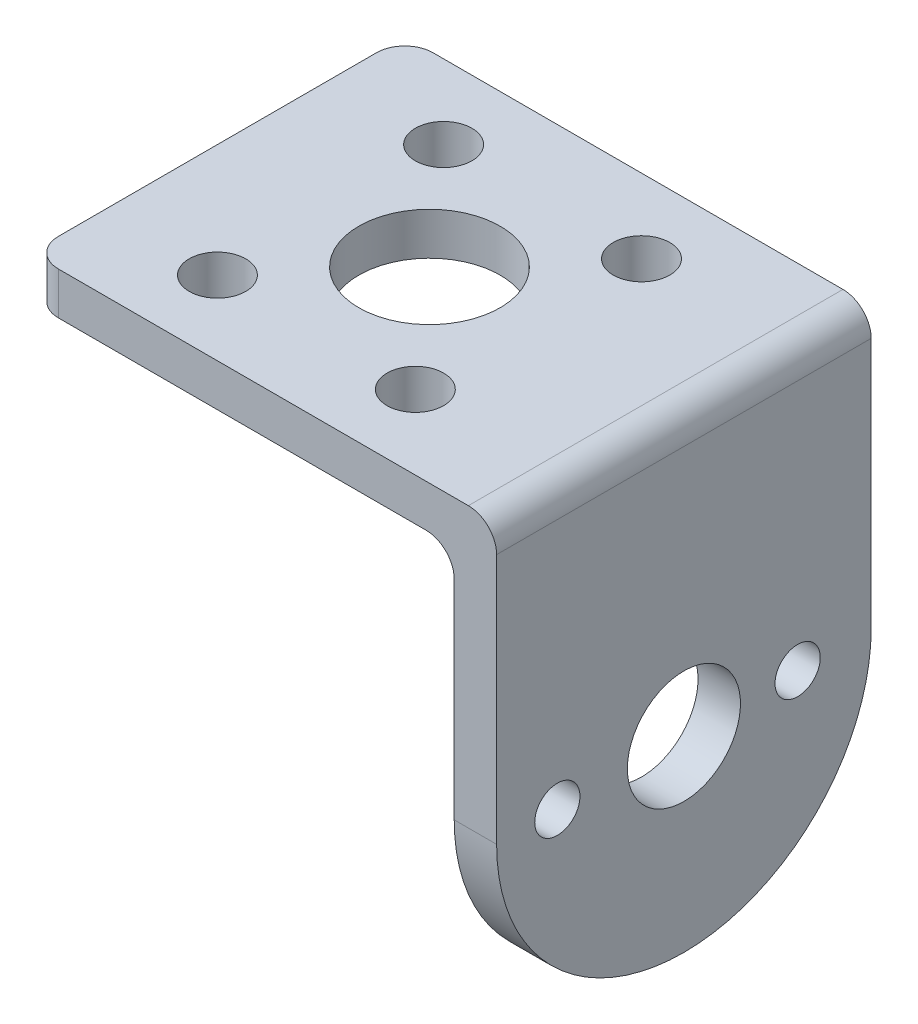
SolidWorks part; units mm, degrees
ref_plane "前视基准面" through (0, 0, 0) normal (0, 0, 1) x (1, 0, 0)
ref_plane "上视基准面" through (0, 0, 0) normal (0, 1, 0) x (1, 0, 0)
ref_plane "右视基准面" through (0, 0, 0) normal (1, 0, 0) x (0, 0, -1)
sketch "草图1" plane through (0, 0, 0) normal (0, 1, 0) x (1, 0, 0)
  line L1 (-25.5407, 12.7704) -> (4.4593, 12.7704)
  line L2 (-25.5407, 12.7704) -> (-25.5407, -13.7296)
  line L3 (-25.5407, -13.7296) -> (4.4593, -13.7296)
  line L4 (4.4593, 12.7704) -> (4.4593, -13.7296)
  point P4 (0, 0)
  point P5 (0, 0)
  point P6 (-30.7928, 14.4611)
  dimension "D1" = 26.5
  dimension "D2" = 30
extrude "凸台-拉伸1" add sketch "草图1" along normal blind 3
sketch "草图2" plane through (0, 3, 0) normal (0, 1, 0) x (1, 0, 0)
  line L0 (4.4593, -13.7296) -> (4.4593, 12.7704) construction
  line L1 (-25.5407, -13.7296) -> (4.4593, -13.7296) construction
  circle A0 centre (-10.5407, -0.4796) radius 5
  point P4 (4.4593, -0.4796)
  point P7 (-10.5407, -13.7296)
  dimension "D1" = 15
  dimension "D2" = 13.25
extrude "切除-拉伸1" cut sketch "草图2" against normal through all
sketch "草图3" plane through (0, 3, 0) normal (0, 1, 0) x (1, 0, 0)
  circle A0 centre (-3.5407, 7.5204) radius 2
  circle A1 centre (-17.5407, 7.5204) radius 2
  circle A2 centre (-3.5407, -8.4796) radius 2
  circle A3 centre (-17.5407, -8.4796) radius 2
  dimension "D1" = 16
  dimension "D2" = 14
extrude "切除-拉伸2" cut sketch "草图3" against normal through all
sketch "草图6" plane through (4.4593, 0, 0) normal (1, 0, 0) x (0, 0, -1)
  line L1 (12.7704, 3) -> (-13.7296, 3)
  line L2 (12.7704, 3) -> (12.7704, -16.75)
  line L4 (-13.7296, 3) -> (-13.7296, -16.75)
  arc A0 (-13.7296, -16.75) -> (12.7704, -16.75) centre (-0.4796, -16.75) ccw
  dimension "D1" = 19.75
  dimension "D2" = 26.5
extrude "凸台-拉伸3" add sketch "草图6" along normal blind 3
sketch "草图7" plane through (4.4593, 0, 0) normal (-1, 0, 0) x (0, 0, 1)
  circle A0 centre (0.4796, -16.75) radius 4
  circle A1 centre (9.4328, -16.75) radius 1.6
  circle A2 centre (-7.5672, -16.75) radius 1.6
  point P7 (0, 0)
  dimension "D1" = 17
extrude "切除-拉伸3" cut sketch "草图7" against normal blind 3
fillet "圆角1" radius 2 2 edges at (-25.5407, 1.5, -12.7704) (-25.5407, 1.5, 13.7296)
fillet "圆角2" radius 2 2 edges at (4.4593, 0, 0.4796) (7.4593, 3, 0.4796)
